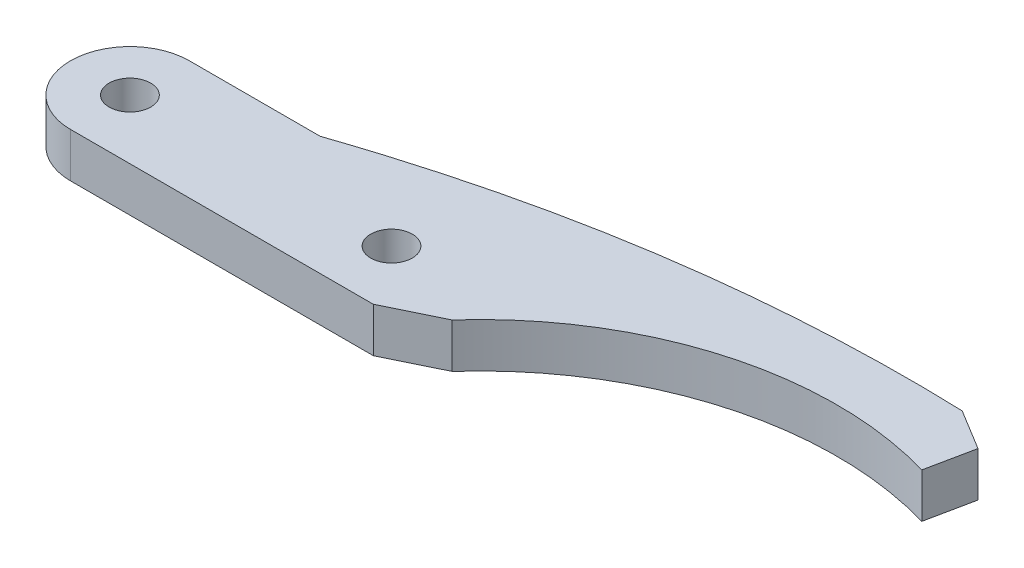
SolidWorks part; units mm, degrees
ref_plane "前视基准面" through (0, 0, 0) normal (0, 0, 1) x (1, 0, 0)
ref_plane "上视基准面" through (0, 0, 0) normal (0, 1, 0) x (1, 0, 0)
ref_plane "右视基准面" through (0, 0, 0) normal (1, 0, 0) x (0, 0, -1)
other "Configuration Table"
sketch "草图1" plane through (0, 0, 0) normal (0, 1, 0) x (1, 0, 0)
  line L1 (108, -20) -> (-20, -20)
  line L2 (108, -20) -> (108, 20)
  line L3 (108, 20) -> (-20, 20)
  line L4 (-20, -20) -> (-20, 20)
  line L5 (108, -20) -> (-20, 20) construction
  line L6 (108, 20) -> (-20, -20) construction
  circle A0 centre (0, 0) radius 7
  circle A1 centre (0, 0) radius 20
  circle A2 centre (88, 0) radius 7
  circle A3 centre (88, 0) radius 20
  point P7 (44, 0)
  dimension "D1" = 40
  dimension "D2" = 14
  dimension "D3" = 88
extrude "凸台-拉伸1" add sketch "草图1" along normal blind 10 contours A1 A0 | A3 L3 A1 L1 | A3 A2
sketch "草图2" plane through (0, 10, 0) normal (0, 1, 0) x (1, 0, 0)
  line L0 (88, -20) -> (101.9108, -20)
  line L1 (101.9108, -20) -> (119.7441, -11.3021)
  line L2 (88, 20) -> (0, 20) construction
  line L3 (232, 48) -> (245.66, 39.6691)
  line L4 (245.66, 39.6691) -> (242.4226, 24)
  line L5 (88, -20) -> (0, -20) construction
  line L8 (0, -20) -> (88, -20)
  line L9 (88, 20) -> (0, 20)
  line L11 (88, 20) -> (44, 20)
  arc A0 (119.7441, -11.3021) -> (242.4226, 24) centre (209.1843, -91.3049) cw
  circle A1 centre (88, 0) radius 7 construction
  arc A4 (0, 20) -> (0, -20) centre (0, 0) ccw
  arc A5 (88, -20) -> (88, 20) centre (88, 0) ccw
  arc A7 (88, -20) -> (88, 20) centre (88, 0) ccw
  spline S0 degree 2 poles (44, 20) (135.7658, 51.2363) (232, 48) knots 0 0 0 1 1 1
  dimension "D6" = 144
  dimension "D7" = 120
  dimension "D1" = 16
  dimension "D2" = 16
  dimension "D3" = 68
  dimension "D4" = 44
  dimension "D5" = 26
  dimension "D8" = 0
extrude "凸台-拉伸2" add sketch "草图2" against normal blind 10
sketch "草图3" plane through (0, 10, 0) normal (0, 1, 0) x (1, 0, 0)
  line L0 (245.66, 39.6691) -> (232, 48) construction
  line L1 (242.4226, 24) -> (245.66, 39.6691) construction
  line L2 (101.9108, -20) -> (119.7441, -11.3021) construction
  line L3 (101.9108, -20) -> (0, -20) construction
  line L4 (44, 20) -> (0, 20) construction
  line L5 (245.66, 39.6691) -> (232, 48)
  line L6 (242.4226, 24) -> (245.66, 39.6691)
  line L7 (101.9108, -20) -> (119.7441, -11.3021)
  line L8 (101.9108, -20) -> (0, -20)
  line L9 (44, 20) -> (0, 20)
  arc A0 (242.4226, 24) -> (119.7441, -11.3021) centre (209.1843, -91.3049) ccw construction
  arc A1 (0, 20) -> (0, -20) centre (0, 0) ccw construction
  circle A2 centre (88, 0) radius 7 construction
  circle A3 centre (0, 0) radius 7 construction
  arc A4 (242.4226, 24) -> (119.7441, -11.3021) centre (209.1843, -91.3049) ccw
  arc A5 (0, 20) -> (0, -20) centre (0, 0) ccw
  circle A6 centre (88, 0) radius 7
  circle A7 centre (0, 0) radius 7
  parabola Q0 (232, 48) -> (44, 20) focus (180.0207, -213.608) apex (146.6318, 43.9758) construction
  parabola Q1 (232, 48) -> (44, 20) focus (180.0207, -213.608) apex (146.6318, 43.9758)
extrude "凸台-拉伸3" add sketch "草图3" along normal blind 10
sketch "草图4" plane through (0, 20, 0) normal (0, 1, 0) x (1, 0, 0)
  line L5 (242.4226, 24) -> (245.66, 39.6691)
  line L6 (245.66, 39.6691) -> (232, 48)
  line L7 (44, 20) -> (0, 20)
  line L8 (0, -20) -> (101.9108, -20)
  line L9 (101.9108, -20) -> (119.7441, -11.3021)
  line L10 (242.4226, 24) -> (245.66, 39.6691)
  line L11 (245.66, 39.6691) -> (232, 48)
  line L12 (44, 20) -> (0, 20)
  line L13 (0, -20) -> (101.9108, -20)
  line L14 (101.9108, -20) -> (119.7441, -11.3021)
  circle A0 centre (0, 0) radius 7 construction
  circle A1 centre (0, 0) radius 7
  arc A2 (0, 20) -> (0, -20) centre (0, 0) ccw
  arc A3 (242.4226, 24) -> (119.7441, -11.3021) centre (209.1843, -91.3049) ccw
  arc A4 (0, 20) -> (0, -20) centre (0, 0) ccw
  arc A5 (242.4226, 24) -> (119.7441, -11.3021) centre (209.1843, -91.3049) ccw
  circle A6 centre (88, 0) radius 7 construction
  circle A7 centre (88, 0) radius 7
  parabola Q1 (232, 48) -> (44, 20) focus (180.0207, -213.608) apex (146.6318, 43.9758)
  parabola Q2 (232, 48) -> (44, 20) focus (180.0207, -213.608) apex (146.6318, 43.9758)
  dimension "D1" = 0
extrude "切除-拉伸1" cut sketch "草图4" against normal blind 5
